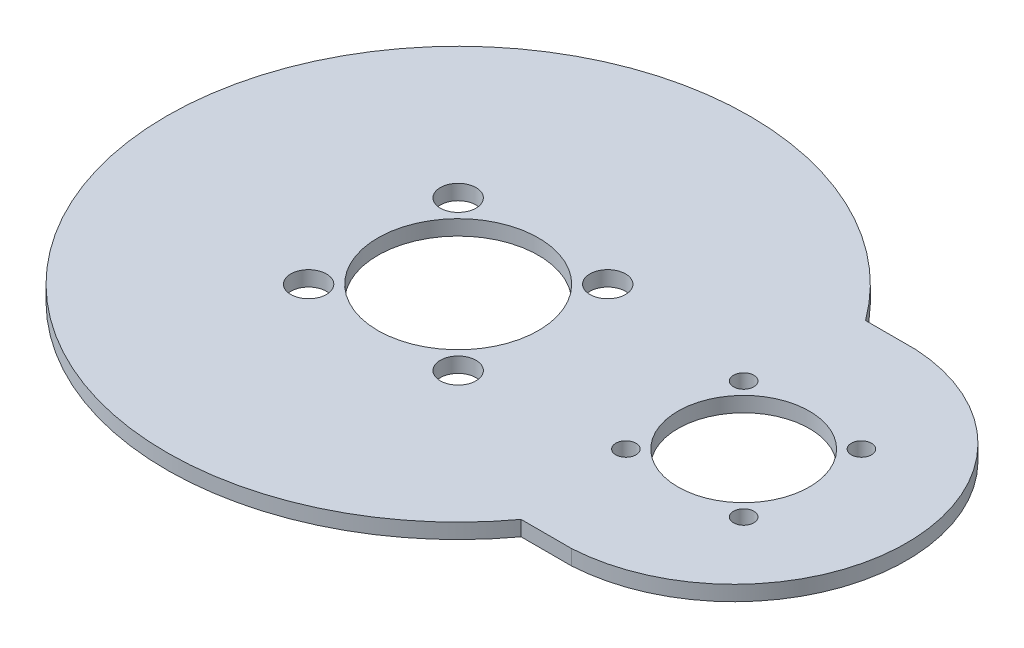
SolidWorks part; units mm, degrees
material "1060 Alloy"
ref_plane "Front Plane" through (0, 0, 0) normal (0, 0, 1) x (1, 0, 0)
ref_plane "Top Plane" through (0, 0, 0) normal (0, 1, 0) x (1, 0, 0)
ref_plane "Right Plane" through (0, 0, 0) normal (1, 0, 0) x (0, 0, -1)
sketch "Sketch1" plane through (0, 0, 0) normal (0, 1, 0) x (1, 0, 0)
  line L0 (41, 0) -> (-41, 0) construction
  line L9 (0, -49) -> (0, 49) construction
  line L10 (0, 0) -> (-12.5724, 12.5724) construction
  line L37 (48, 0) -> (38.1005, 9.8995) construction
  line L38 (48, -28.955) -> (48, 28.955) construction
  line L39 (48, -28.955) -> (29.0277, -28.955) construction
  line L40 (39.5298, -28.955) -> (48, -28.955)
  line L41 (48, 28.955) -> (29.0277, 28.955) construction
  line L42 (39.5298, 28.955) -> (48, 28.955)
  circle A1 centre (0, 0) radius 17.78 construction
  circle A2 centre (0, 0) radius 41 construction
  circle A3 centre (48, 0) radius 11.05
  circle A4 centre (-12.5724, 12.5724) radius 3
  circle A5 centre (12.5724, 12.5724) radius 3
  circle A6 centre (12.5724, -12.5724) radius 3
  circle A7 centre (-12.5724, -12.5724) radius 3
  circle A8 centre (0, 0) radius 13.5
  circle A9 centre (48, 0) radius 14 construction
  circle A10 centre (38.1005, 9.8995) radius 1.7
  circle A11 centre (57.8995, 9.8995) radius 1.7
  circle A12 centre (57.8995, -9.8995) radius 1.7
  circle A13 centre (38.1005, -9.8995) radius 1.7
  arc A15 (48, 28.955) -> (48, -28.955) centre (46.3854, 0) cw
  arc A16 (0, 49) -> (0, -49) centre (0, 0) ccw
  arc A17 (0, -49) -> (39.5298, -28.955) centre (0, 0) ccw
  arc A18 (0, 49) -> (39.5298, 28.955) centre (0, 0) cw
  point P4 (48, 0)
  point P16 (0, 0)
  point P21 (0, 0)
  point P26 (0, 0)
  point P40 (48, 0)
  dimension "D4" = 35.56
  dimension "D9" = 82
  dimension "D7" = 27
  dimension "D1" = 22.1
  dimension "D2" = 6
  dimension "D8" = 28
  dimension "D11" = 3.4
  dimension "D13" = 29
  dimension "D14" = 49
  dimension "D3" = 4
  dimension "D5" = 45
  dimension "D6" = 48
  dimension "D10" = 45
  dimension "D12" = 4
extrude "Boss-Extrude1" add sketch "Sketch1" along normal blind 2.54 contours A18 A16 A17 L40 A15 L42 A13 A12 A11 A10 A8 A7 A6 A5 A4 A3
